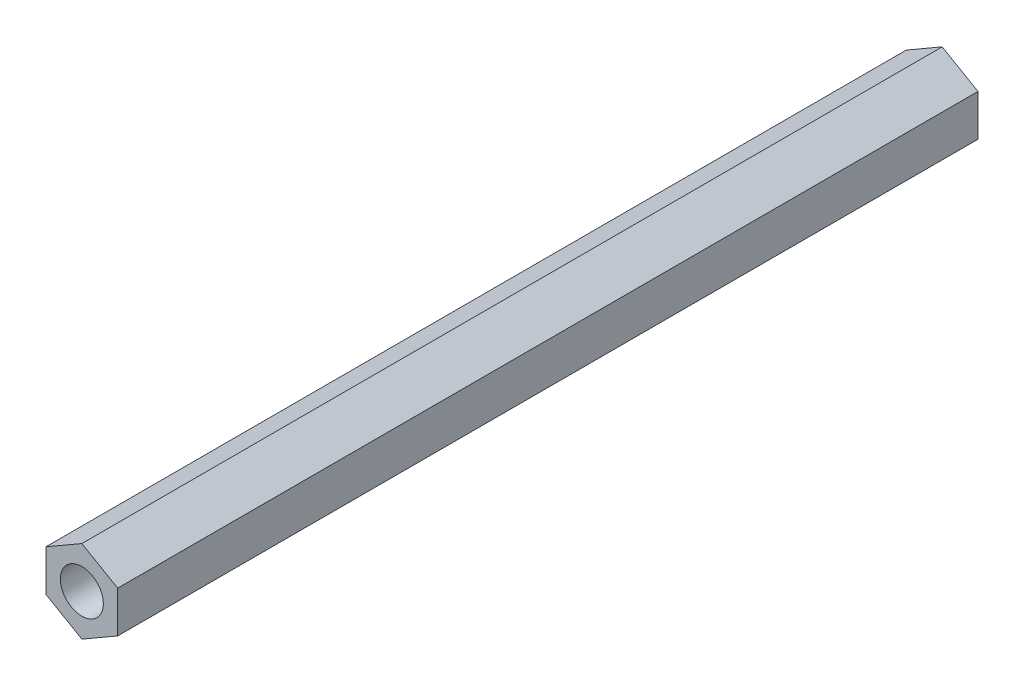
SolidWorks part; units mm, degrees
ref_plane "前视基准面" through (0, 0, 0) normal (0, 0, 1) x (1, 0, 0)
ref_plane "上视基准面" through (0, 0, 0) normal (0, 1, 0) x (1, 0, 0)
ref_plane "右视基准面" through (0, 0, 0) normal (1, 0, 0) x (0, 0, -1)
other "Configuration Table"
sketch "草图1" plane through (0, 0, 0) normal (0, 0, 1) x (1, 0, 0)
  line L0 (0, 0) -> (0, 3.8105) construction
  line L1 (0, 2.8868) -> (-2.5, 1.4434)
  line L2 (0, 1.7321) -> (-1.5, 0.866) construction
  line L3 (-1.5, 0.866) -> (-1.5, -0.866) construction
  line L4 (-1.5, -0.866) -> (0, -1.7321) construction
  line L5 (0, -1.7321) -> (1.5, -0.866) construction
  line L6 (1.5, -0.866) -> (1.5, 0.866) construction
  line L7 (1.5, 0.866) -> (0, 1.7321) construction
  line L8 (-2.5, 1.4434) -> (-2.5, -1.4434)
  line L9 (-2.5, -1.4434) -> (0, -2.8868)
  line L10 (0, -2.8868) -> (2.5, -1.4434)
  line L11 (2.5, -1.4434) -> (2.5, 1.4434)
  line L12 (2.5, 1.4434) -> (0, 2.8868)
  circle A0 centre (0, 0) radius 1.5
  dimension "D1" = 3
  dimension "D2" = 1
extrude "凸台-拉伸1" add sketch "草图1" along normal blind 60
